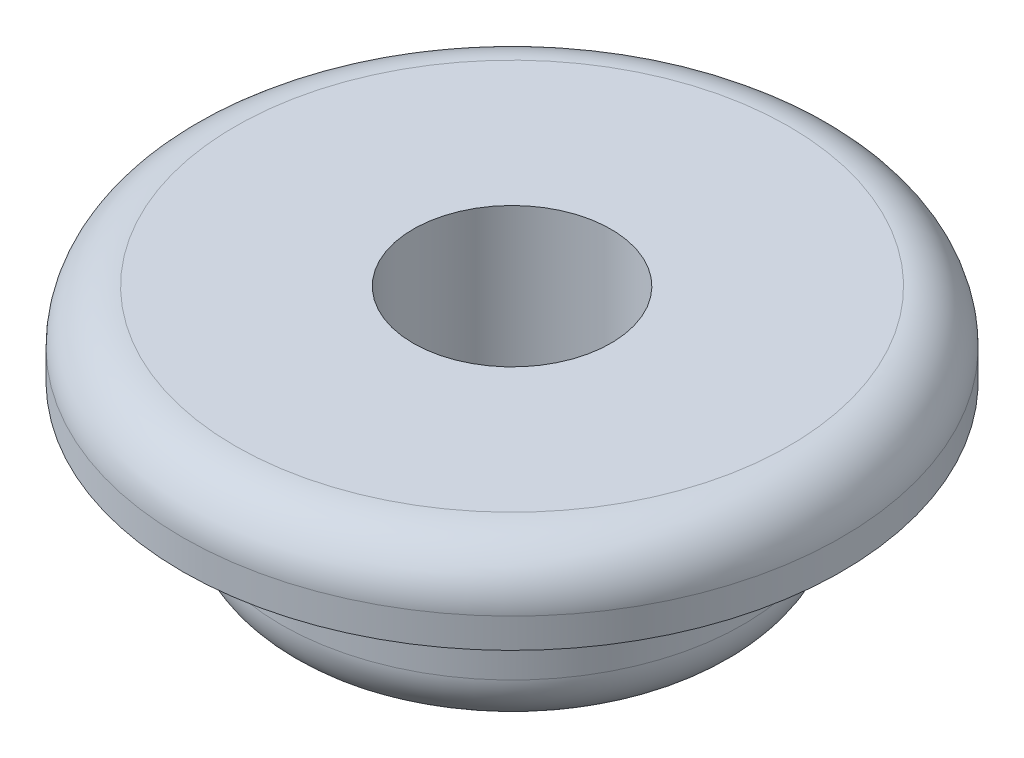
SolidWorks part; units mm, degrees
material "Rubber"
ref_plane "Front Plane" through (0, 0, 0) normal (0, 0, 1) x (1, 0, 0)
ref_plane "Top Plane" through (0, 0, 0) normal (0, 1, 0) x (1, 0, 0)
ref_plane "Right Plane" through (0, 0, 0) normal (1, 0, 0) x (0, 0, -1)
sketch "Sketch1" plane through (0, 0, 0) normal (0, 1, 0) x (1, 0, 0)
  circle A0 centre (0, 0) radius 5.5563
  dimension "D1" = 11.1125
extrude "Boss-Extrude1" add sketch "Sketch1" along normal mid plane 5.5562
sketch "Sketch2" plane through (0, 2.7781, 0) normal (0, 1, 0) x (1, 0, 0)
  circle A0 centre (0, 0) radius 7.9375
  dimension "D1" = 15.875
extrude "Boss-Extrude2" add sketch "Sketch2" against normal blind 2.54
sketch "Sketch3" plane through (0, 0, 0) normal (0, 1, 0) x (1, 0, 0)
  circle A0 centre (0, 0) radius 3.9688
  circle A1 centre (0, 0) radius 8.0708
  dimension "D1" = 7.9375
extrude "Cut-Extrude1" cut sketch "Sketch3" against normal mid plane 1.5875
sketch "Sketch4" plane through (0, 2.7781, 0) normal (0, 1, 0) x (1, 0, 0)
  circle A0 centre (0, 0) radius 2.3813
  dimension "D1" = 4.7625
extrude "Cut-Extrude2" cut sketch "Sketch4" against normal through all
fillet "Fillet1" radius 1.27 2 edges at (0, 2.7781, 7.9375) (0, -2.7781, 5.5563)
